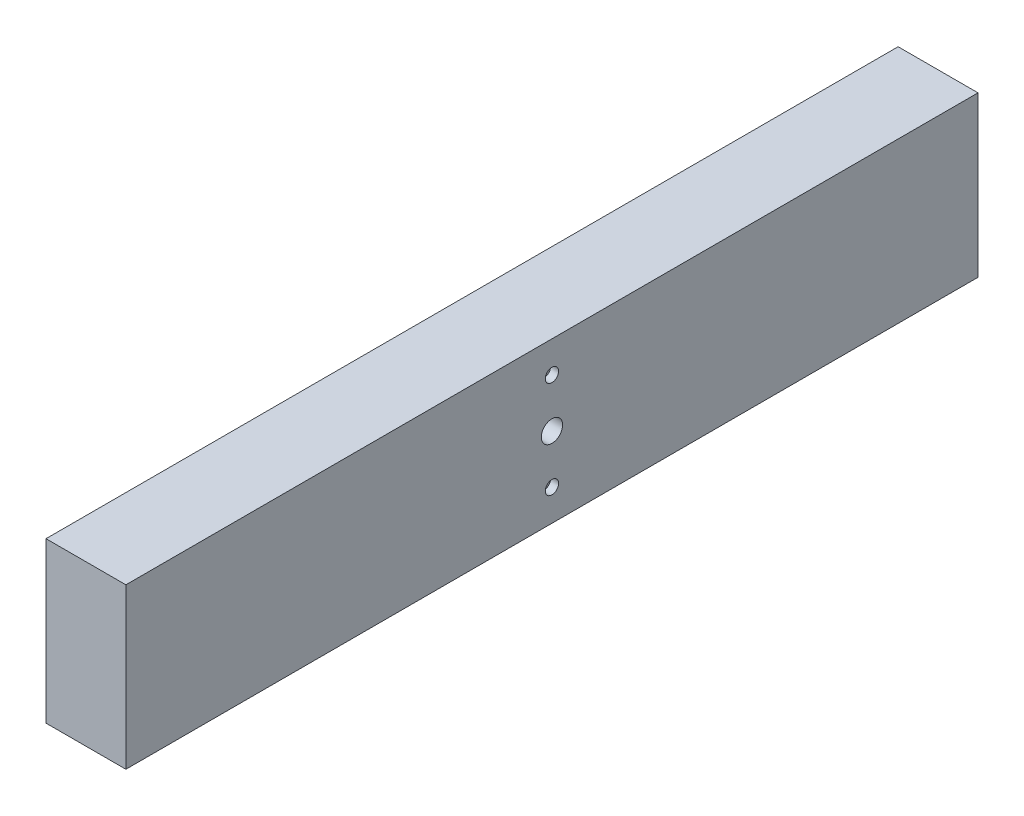
SolidWorks part; units mm, degrees
ref_plane "Front Plane" through (0, 0, 0) normal (0, 0, 1) x (1, 0, 0)
ref_plane "Top Plane" through (0, 0, 0) normal (0, 1, 0) x (1, 0, 0)
ref_plane "Right Plane" through (0, 0, 0) normal (1, 0, 0) x (0, 0, -1)
sketch "Sketch1" plane through (0, 0, 0) normal (0, 0, 1) x (1, 0, 0)
  line L1 (-15, -30) -> (15, -30)
  line L2 (-15, -30) -> (-15, 30)
  line L3 (-15, 30) -> (15, 30)
  line L4 (15, -30) -> (15, 30)
  line L5 (-15, -30) -> (15, 30) construction
  line L6 (-15, 30) -> (15, -30) construction
  point P0 (0, 0)
  dimension "D1" = 60
  dimension "D2" = 30
extrude "Boss-Extrude1" add sketch "Sketch1" along normal mid plane 320
sketch "Sketch2" plane through (15, 0, 0) normal (1, 0, 0) x (0, 0, -1)
  line L0 (-160, 0) -> (160, 0) construction
  line L1 (-160, -30) -> (-160, 30) construction
  line L2 (160, -30) -> (160, 30) construction
  line L3 (0, 30) -> (0, -30) construction
  line L4 (-160, 30) -> (160, 30) construction
  line L5 (-160, -30) -> (160, -30) construction
  circle A0 centre (0, 18.25) radius 2.5
  circle A1 centre (0, -18.25) radius 2.5
  dimension "D1" = 5
  dimension "D2" = 36.5
extrude "Cut-Extrude1" cut sketch "Sketch2" against normal blind 3
sketch "Sketch3" plane through (15, 0, 0) normal (1, 0, 0) x (0, 0, -1)
  line L0 (0, 30) -> (0, -30) construction
  line L1 (-160, 30) -> (160, 30) construction
  line L2 (-160, -30) -> (160, -30) construction
  circle A0 centre (0, 0) radius 4
  dimension "D1" = 8
extrude "Cut-Extrude2" cut sketch "Sketch3" against normal blind 10
